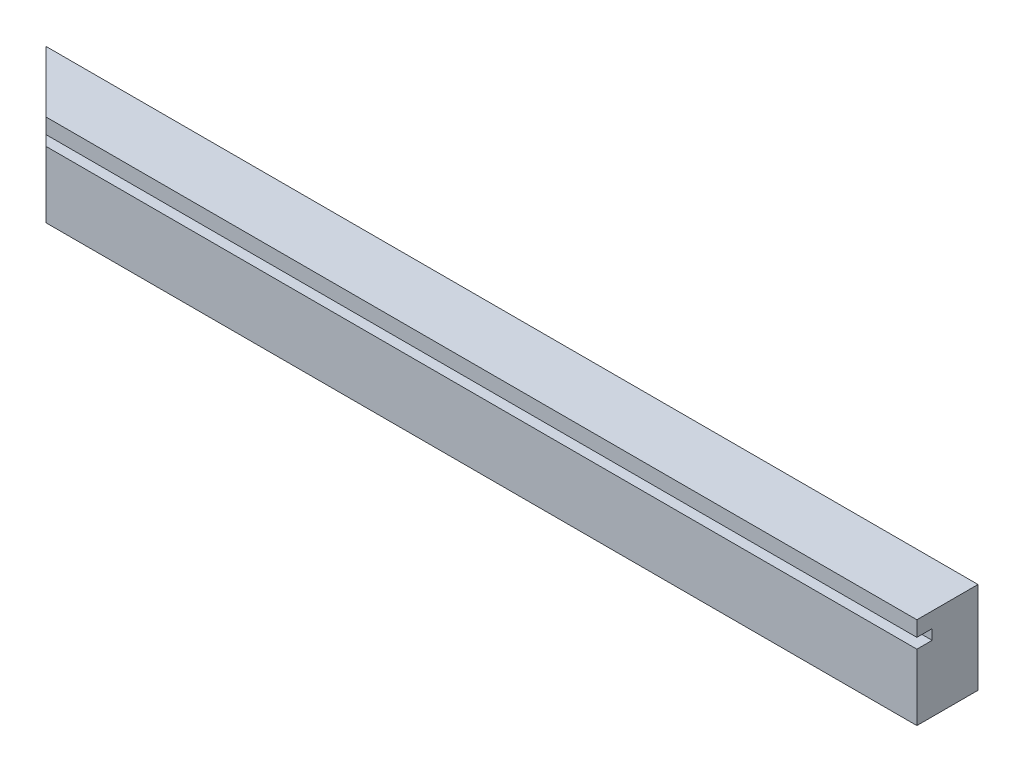
SolidWorks part; units mm, degrees
ref_plane "Front Plane" through (0, 0, 0) normal (0, 0, 1) x (1, 0, 0)
ref_plane "Top Plane" through (0, 0, 0) normal (0, 1, 0) x (1, 0, 0)
ref_plane "Right Plane" through (0, 0, 0) normal (1, 0, 0) x (0, 0, -1)
sketch "Sketch1" plane through (0, 0, 0) normal (0, 1, 0) x (1, 0, 0)
  line L0 (0, 0) -> (12, 12)
  line L1 (12, 12) -> (183, 12)
  line L2 (183, 12) -> (183, 0)
  line L3 (183, 0) -> (0, 0)
  line L4 (0, 0) -> (0, 0.7121)
  dimension "D1" = 171
  dimension "D2" = 12
  dimension "D3" = 45
  dimension "D4" = 183
extrude "Boss-Extrude1" add sketch "Sketch1" along normal blind 18 contours L3 L2 L1 L0
sketch "Sketch2" plane through (183, 0, 0) normal (1, 0, 0) x (0, 0, -1)
  line L1 (12, 13) -> (9, 13)
  line L2 (12, 15) -> (0, 15)
  line L3 (12, 15) -> (9, 15)
  line L5 (12, 13) -> (0, 13) construction
  line L6 (9, 18) -> (9, 0)
  line L7 (9, 15) -> (9, 13)
  line L8 (12, 15) -> (0, 15) construction
  dimension "D1" = 3
  dimension "D2" = 3
extrude "Cut-Extrude1" cut sketch "Sketch2" against normal through all and the other way through all
mirror "Mirror2" about plane through (0, 18, -12) normal (0, 0, -1) of "Boss-Extrude1", "Cut-Extrude1"
sketch "Sketch3" plane through (0, 0, 0) normal (0, 0, 1) x (1, 0, 0)
  line L4 (0, 0) -> (183, 0)
  line L5 (183, 0) -> (183, 18)
  line L6 (183, 18) -> (0, 18)
  line L7 (0, 18) -> (0, 0)
  line L8 (0, 0) -> (183, 0)
  line L9 (183, 0) -> (183, 18)
  line L10 (183, 18) -> (0, 18)
  line L11 (0, 18) -> (0, 0)
  dimension "D1" = 0
extrude "Cut-Extrude2" cut sketch "Sketch3" against normal blind 12
